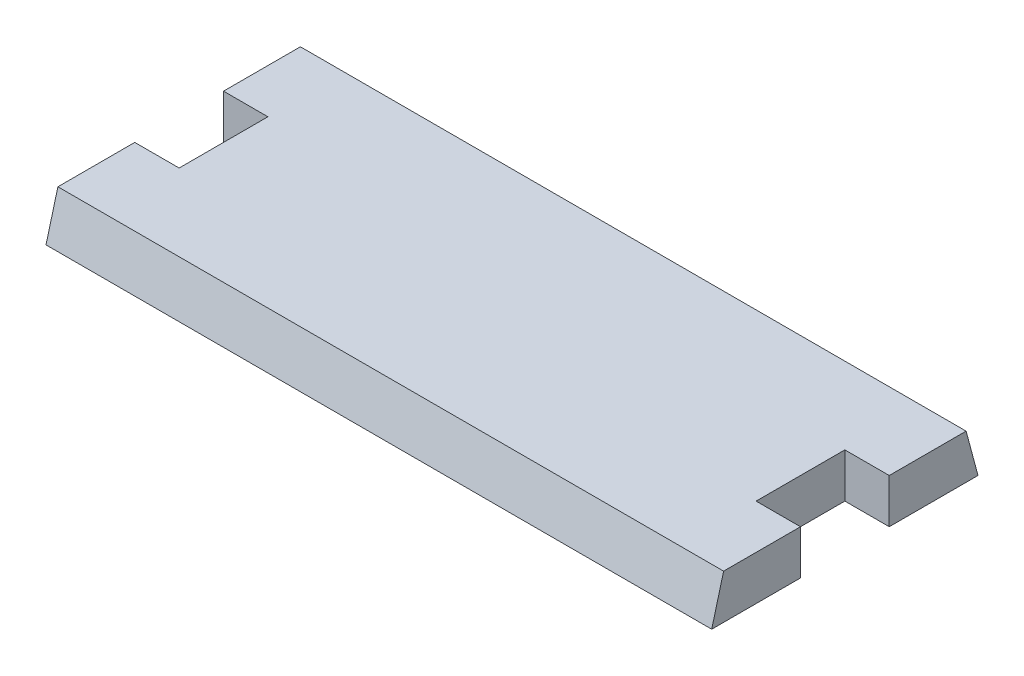
SolidWorks part; units mm, degrees
ref_plane "Front Plane" through (0, 0, 0) normal (0, 0, 1) x (1, 0, 0)
ref_plane "Top Plane" through (0, 0, 0) normal (0, 1, 0) x (1, 0, 0)
ref_plane "Right Plane" through (0, 0, 0) normal (1, 0, 0) x (0, 0, -1)
sketch "Sketch1" plane through (0, 0, 0) normal (0, 1, 0) x (1, 0, 0)
  line L0 (75, 10) -> (75, 30)
  line L1 (-75, -30) -> (75, -30)
  line L2 (-75, -30) -> (-75, -10)
  line L3 (-75, 30) -> (75, 30)
  line L4 (75, -30) -> (75, -10)
  line L5 (-75, -30) -> (75, 30) construction
  line L6 (-75, 30) -> (75, -30) construction
  line L7 (75, 10) -> (65, 10)
  line L9 (75, -10) -> (65, -10)
  line L10 (65, 10) -> (65, -10)
  line L11 (0, 0) -> (0, 30) construction
  line L12 (-75, -10) -> (-65, -10)
  line L13 (-75, 10) -> (-65, 10)
  line L14 (-65, 10) -> (-65, -10)
  line L15 (-75, 10) -> (-75, 30)
  point P0 (0, 0)
  dimension "D1" = 150
  dimension "D2" = 60
  dimension "D3" = 10
  dimension "D4" = 20
  dimension "D5" = 20
extrude "Boss-Extrude1" add sketch "Sketch1" along normal blind 10
draft "Draft5" type of draft neutral plane draft angle 15 faces to draft 2 face at (0, 5, -30) face at (0, 5, 30) neutral plane through (0, 0, 0) neutral plane normal (0, -1, 0) reverse direction yes parameters "D1"=15
